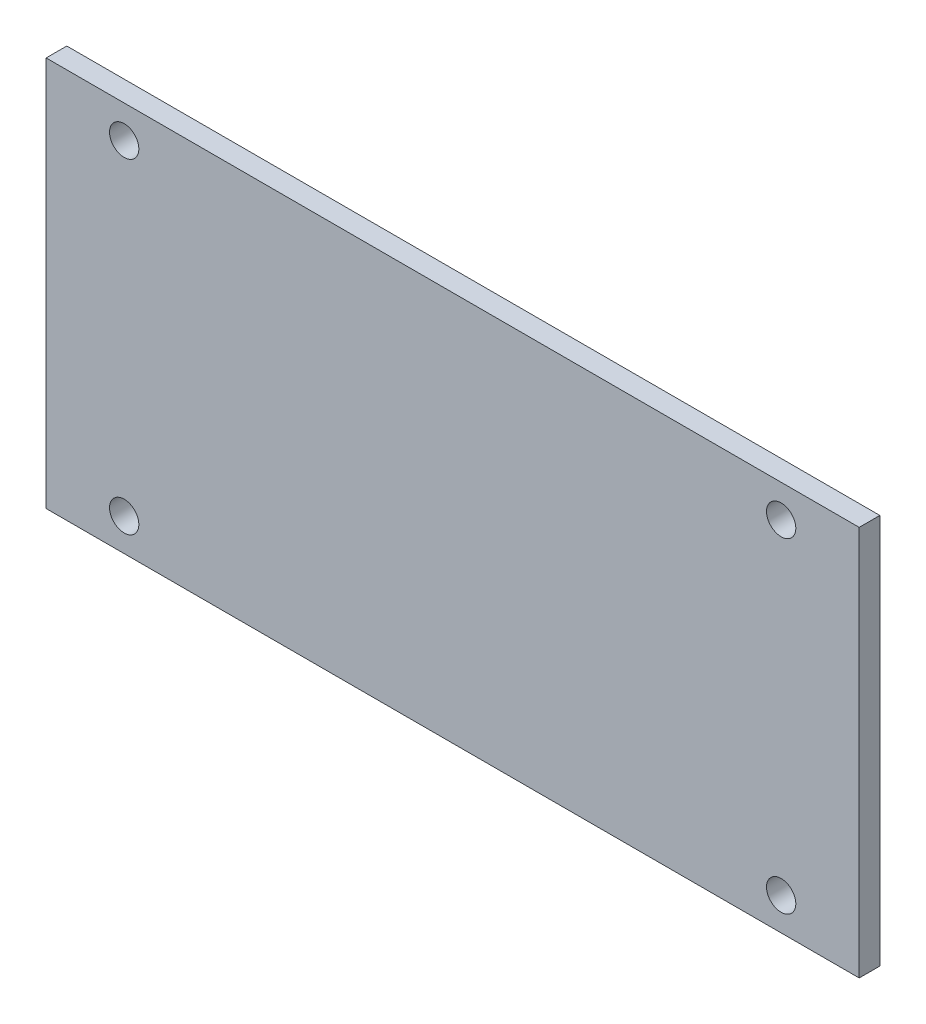
SolidWorks part; units mm, degrees
ref_plane "Plan de face" through (0, 0, 0) normal (0, 0, 1) x (1, 0, 0)
ref_plane "Plan de dessus" through (0, 0, 0) normal (0, 1, 0) x (1, 0, 0)
ref_plane "Plan de droite" through (0, 0, 0) normal (1, 0, 0) x (0, 0, -1)
sketch "Sketch1" plane through (0, 0, 0) normal (0, 0, 1) x (1, 0, 0)
  line L1 (62.5, -30) -> (-62.5, -30)
  line L2 (62.5, -30) -> (62.5, 30)
  line L3 (62.5, 30) -> (-62.5, 30)
  line L4 (-62.5, -30) -> (-62.5, 30)
  line L5 (62.5, -30) -> (-62.5, 30) construction
  line L6 (62.5, 30) -> (-62.5, -30) construction
  point P0 (0, 0)
  dimension "D1" = 125
  dimension "D2" = 60
extrude "Boss-Extrude1" add sketch "Sketch1" along normal blind 3.175
sketch "Sketch2" plane through (0, 0, 3.175) normal (0, 0, 1) x (1, 0, 0)
  line L0 (0, -30) -> (0, 30) construction
  line L1 (-62.5, -30) -> (62.5, -30) construction
  line L2 (62.5, 30) -> (-62.5, 30) construction
  line L3 (-62.5, 30) -> (-62.5, -30) construction
  circle A0 centre (-50.5, 25) radius 2.25
  circle A1 centre (-50.5, -25) radius 2.25
  circle A4 centre (50.5, -25) radius 2.25
  circle A5 centre (50.5, 25) radius 2.25
  point P14 (0, 0)
  point P15 (-58.6715, -27.0158)
  dimension "D5" = 4.5
  dimension "D6" = 4.5
  dimension "D1" = 5
  dimension "D2" = 12
  dimension "D3" = 12
  dimension "D4" = 5
extrude "Cut-Extrude2" cut sketch "Sketch2" against normal blind 3.175
